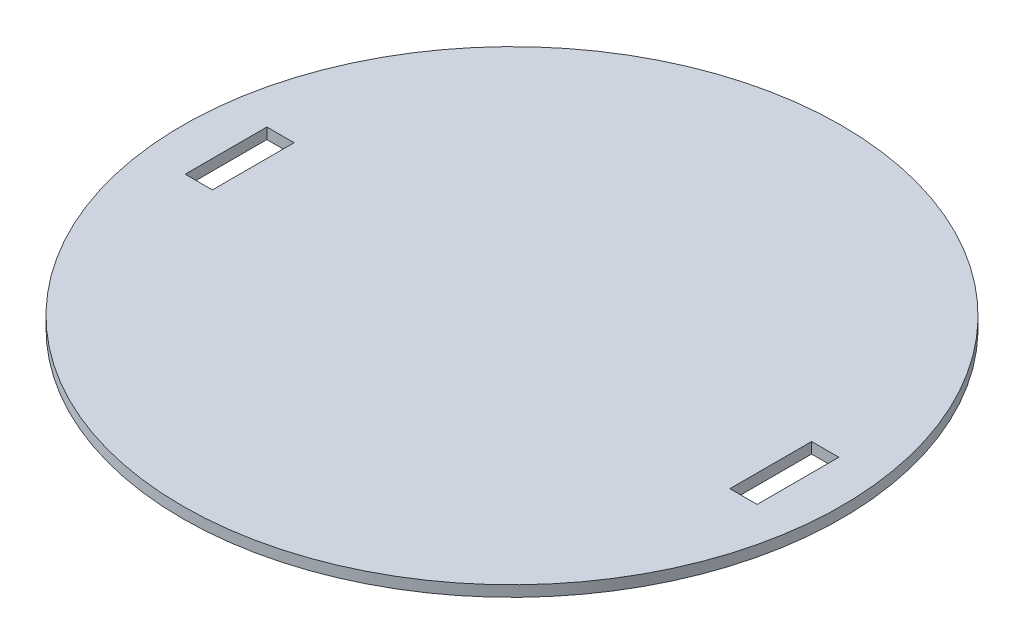
SolidWorks part; units mm, degrees
ref_plane "Front Plane" through (0, 0, 0) normal (0, 0, 1) x (1, 0, 0)
ref_plane "Top Plane" through (0, 0, 0) normal (0, 1, 0) x (1, 0, 0)
ref_plane "Right Plane" through (0, 0, 0) normal (1, 0, 0) x (0, 0, -1)
sketch "Bottom" plane through (0, 0, 0) normal (0, 1, 0) x (-1, 0, 0)
  line L0 (0, 0) -> (100, 0) construction
  line L1 (0, 2.2) -> (0, -2.2) construction
  line L2 (105, -15) -> (95, -15)
  line L3 (105, -15) -> (105, 15)
  line L4 (105, 15) -> (95, 15)
  line L5 (95, -15) -> (95, 15)
  line L6 (105, -15) -> (95, 15) construction
  line L7 (105, 15) -> (95, -15) construction
  line L8 (-105, 15) -> (-95, 15)
  line L9 (-95, -15) -> (-95, 15)
  line L10 (-105, -15) -> (-95, -15)
  line L11 (-105, -15) -> (-105, 15)
  line L12 (-105, 15) -> (-95, -15) construction
  line L13 (-105, -15) -> (-95, 15) construction
  circle A0 centre (0, 0) radius 121
  point P8 (0, 0)
  dimension "D1" = 242
  dimension "D2" = 100
  dimension "D3" = 30
  dimension "D4" = 10
extrude "Bottom-Extrude" add sketch "Bottom" along normal blind 4
equation "\"inner radius\"= 230"
equation "\"wall thickness\"= 6\t"
equation "\"outer radius\"= \"inner radius\" + 2 * \"wall thickness\""
equation "\"height\" = 40"
equation "\"D1@Bottom\"=\"outer radius\""
equation "\"wheel distance\" = 100"
equation "\"D2@Bottom\"=\"wheel distance\""
equation "\"screw length\" = 15"
equation "\"top bottom thickness\" = 4"
equation "\"D1@Bottom-Extrude\"=\"top bottom thickness\""
equation "\"accel distance\" = 75"
equation "\"tolerance\" = 0.1"
equation "\"wheel hole width\" = 30"
equation "\"D3@Bottom\"=\"wheel hole width\""
